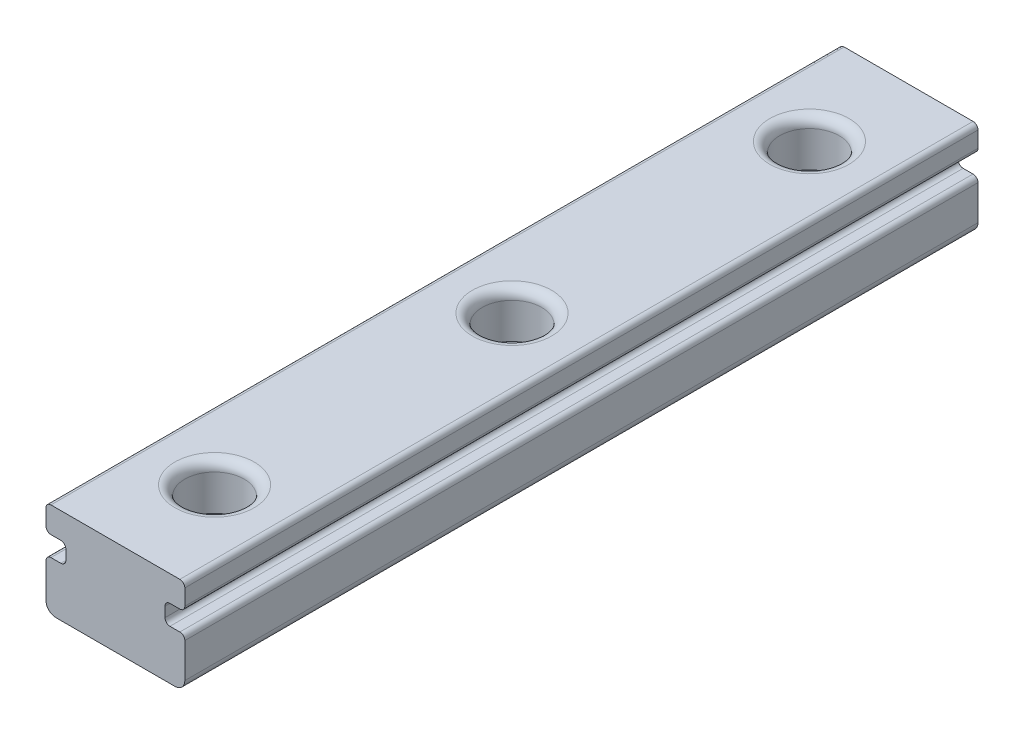
SolidWorks part; units mm, degrees
material "201 退火不锈钢 (SS)"
ref_plane "前视基准面" through (0, 0, 0) normal (0, 0, 1) x (1, 0, 0)
ref_plane "上视基准面" through (0, 0, 0) normal (0, 1, 0) x (1, 0, 0)
ref_plane "右视基准面" through (0, 0, 0) normal (1, 0, 0) x (0, 0, -1)
sketch "草图1" plane through (0, 0, 0) normal (0, 0, 1) x (1, 0, 0)
  line L0 (0, 0) -> (7, 0)
  line L1 (0, 3.5) -> (0, 4.8)
  line L2 (0, 4.8) -> (7, 4.8)
  line L3 (7, 4.8) -> (7, 3.5)
  line L4 (0, 4.8) -> (0, 3.5)
  line L5 (0, 2.5) -> (1, 2.5)
  line L6 (1, 2.5) -> (1, 3.5)
  line L7 (1, 3.5) -> (0, 3.5)
  line L8 (7, 3.5) -> (6, 3.5)
  line L9 (6, 3.5) -> (6, 2.5)
  line L10 (6, 2.5) -> (7, 2.5)
  line L11 (0, 2.5) -> (0, 0)
  line L12 (7, 2.5) -> (7, 0)
extrude "凸台-拉伸1" add sketch "草图1" along normal blind 40 contours L12 L10 L9 L8 L3 L2 L1 L7 L6 L5 L11 L0
fillet "圆角1" radius 0.25 10 edges at (7, 2.5, 20) (0, 2.5, 20) (1, 3.5, 20) (1, 2.5, 20) (6, 2.5, 20) (6, 3.5, 20) (7, 4.8, 20) (0, 4.8, 20) (0, 3.5, 20) (7, 3.5, 20)
fillet "圆角2" radius 0.5 2 edges at (0, 0, 20) (7, 0, 20)
sketch "草图2" plane through (0, 4.8, 0) normal (0, 1, 0) x (1, 0, 0)
  line L0 (0.25, 0) -> (6.75, 0) construction
  line L1 (3.5, 0) -> (3.5, -6.7471) construction
  circle A0 centre (3.5, -5) radius 1.5
  dimension "D1" = 3
  dimension "D2" = 5
extrude "切除-拉伸1" cut sketch "草图2" against normal blind 2.3
sketch "草图3" plane through (0, 2.5, 0) normal (0, 1, 0) x (1, 0, 0)
  line L0 (0.5, 0) -> (6.5, 0) construction
  line L1 (3.5, 0) -> (3.5, -4.4975) construction
  circle A1 centre (3.5, -5) radius 1.2
  dimension "D1" = 2.4
  dimension "D2" = 5
extrude "切除-拉伸2" cut sketch "草图3" against normal through all
fillet "圆角3" radius 0.5 1 edges at (3.5, 4.8, 6.5)
pattern_linear "阵列(线性)2" count 3 spacing 15 along (0, 0, 1) of "切除-拉伸1", "切除-拉伸2", "圆角3"
